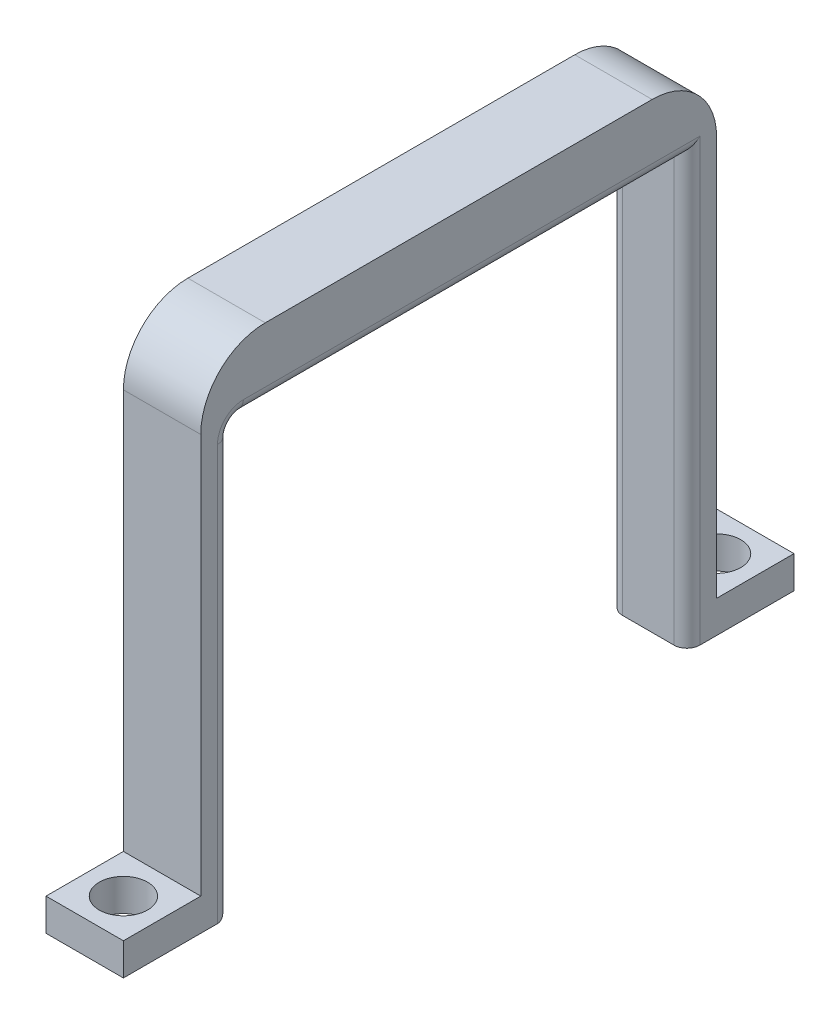
SolidWorks part; units mm, degrees
ref_plane "Front Plane" through (0, 0, 0) normal (0, 0, 1) x (1, 0, 0)
ref_plane "Top Plane" through (0, 0, 0) normal (0, 1, 0) x (1, 0, 0)
ref_plane "Right Plane" through (0, 0, 0) normal (1, 0, 0) x (0, 0, -1)
sketch "Sketch1" plane through (0, 0, 0) normal (1, 0, 0) x (0, 0, -1)
  line L0 (0, 0) -> (21.082, 0)
  line L1 (21.082, 0) -> (21.082, 6.35)
  line L2 (21.082, 6.35) -> (21.082, 84.2884)
  line L3 (110.998, 84.2884) -> (110.998, 0)
  line L4 (110.998, 0) -> (132.08, 0)
  line L5 (132.08, 0) -> (132.08, 6.35)
  line L6 (0, 0) -> (0, 6.35)
  line L7 (0, 6.35) -> (15.24, 6.35)
  line L8 (15.24, 6.35) -> (15.24, 97.79)
  line L9 (15.24, 97.79) -> (116.84, 97.79)
  line L10 (116.84, 97.79) -> (116.84, 6.35)
  line L11 (116.84, 6.35) -> (132.08, 6.35)
  line L12 (21.082, 84.2884) -> (110.998, 84.2884)
  dimension "D1" = 15.24
  dimension "D2" = 15.24
  dimension "D3" = 6.35
  dimension "D4" = 91.44
  dimension "D5" = 89.916
  dimension "D6" = 132.08
  dimension "D8" = 5.842
  dimension "D9" = 6.35
extrude "Boss-Extrude1" add sketch "Sketch1" along normal blind 15.24
fillet "Fillet1" radius 12.7 2 edges at (7.62, 97.79, -116.84) (7.62, 97.79, -15.24)
sketch "Sketch2" plane through (0, 6.35, 0) normal (0, 1, 0) x (1, 0, 0)
  line L0 (15.24, 0) -> (15.24, 15.24) construction
  line L1 (15.24, 0) -> (0, 0) construction
  circle A0 centre (7.62, 7.62) radius 4.7625
  point P5 (15.24, 7.62)
  dimension "D1" = 9.525
  dimension "D2" = 7.62
  dimension "D3" = 7.62
extrude "Cut-Extrude1" cut sketch "Sketch2" against normal blind 17.78
fillet "Fillet2" radius 2.54 8 edges at (15.24, 84.2884, -66.04) (0, 84.2884, -66.04) (15.24, 42.1442, -110.998) (0, 42.1442, -110.998) (7.62, 0, -21.082) (15.24, 42.1442, -21.082) (7.62, 84.2884, -21.082) (0, 42.1442, -21.082)
pattern_linear "LPattern1" count 2 spacing 116.84 along (0, 0, -1) of "Cut-Extrude1"
